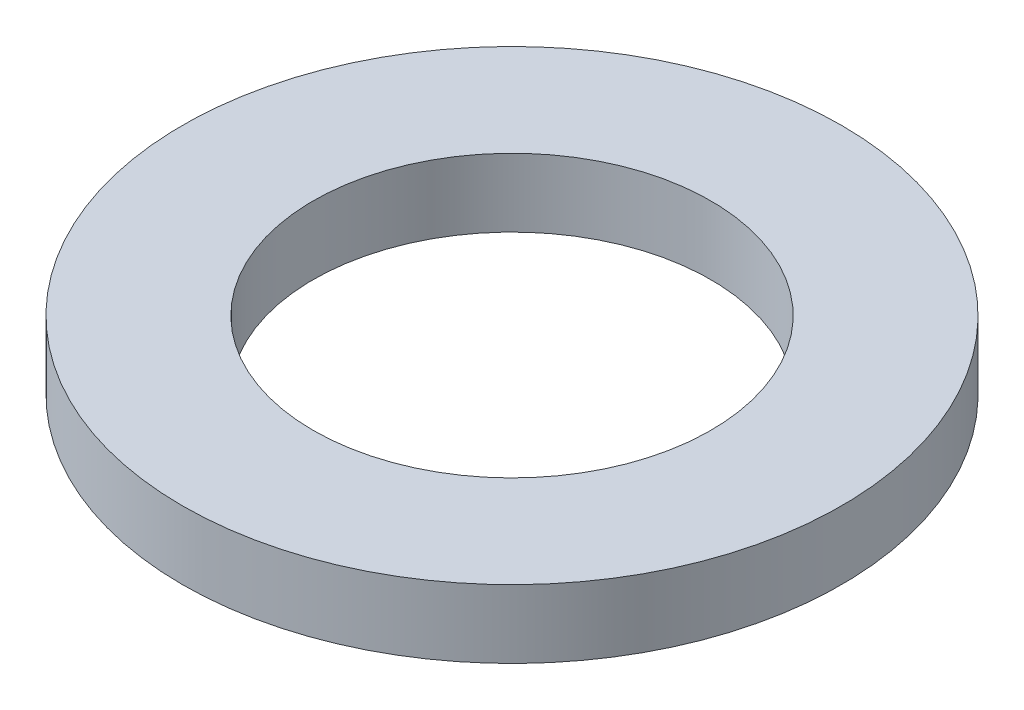
SolidWorks part; units mm, degrees
ref_plane "Front Plane" through (0, 0, 0) normal (0, 0, 1) x (1, 0, 0)
ref_plane "Top Plane" through (0, 0, 0) normal (0, 1, 0) x (1, 0, 0)
ref_plane "Right Plane" through (0, 0, 0) normal (1, 0, 0) x (0, 0, -1)
sketch "Sketch1" plane through (0, 0, 0) normal (0, 1, 0) x (1, 0, 0)
  circle A0 centre (0, 0) radius 9.655
  circle A1 centre (0, 0) radius 5.825
  dimension "D1" = 19.31
  dimension "D2" = 11.65
  dimension "D3" = 11.65
extrude "Boss-Extrude1" add sketch "Sketch1" along normal blind 2 contours A0 | A1
